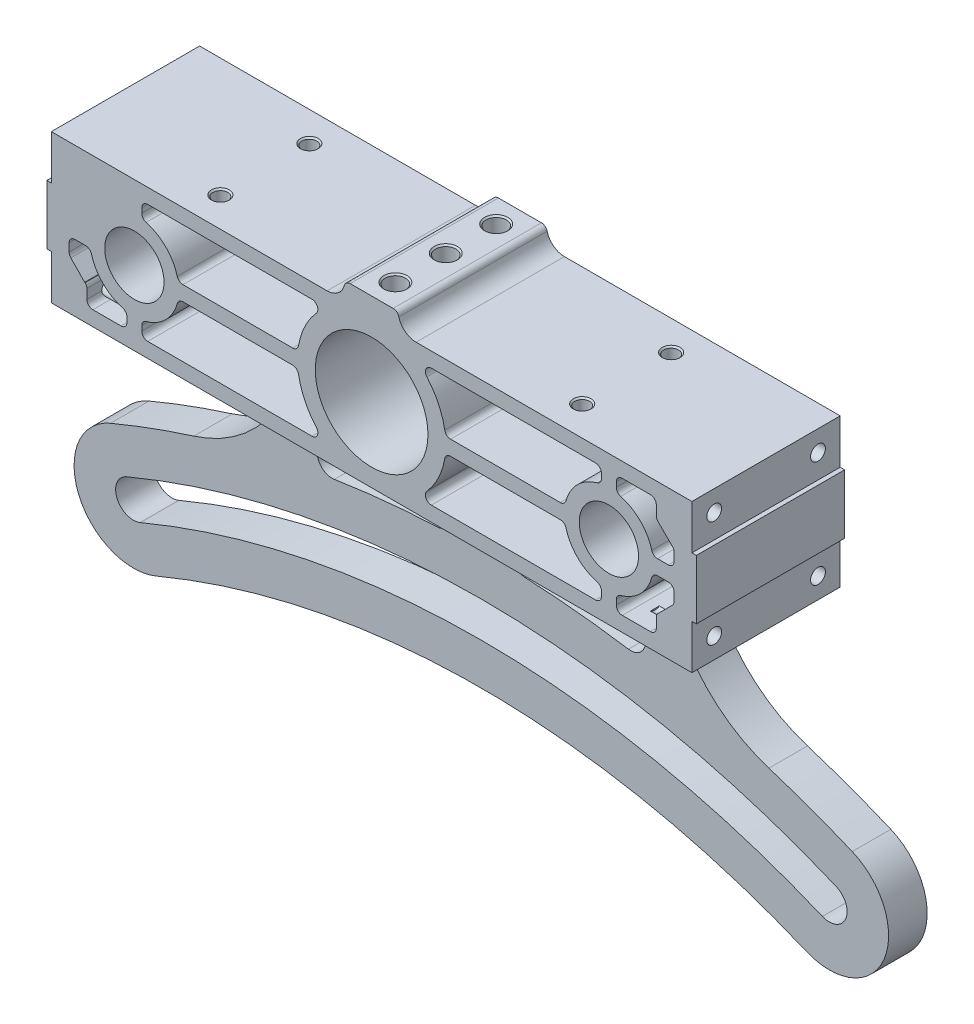
SolidWorks part; units mm, degrees
ref_plane "前视基准面" through (0, 0, 0) normal (0, 0, 1) x (1, 0, 0)
ref_plane "上视基准面" through (0, 0, 0) normal (0, 1, 0) x (1, 0, 0)
ref_plane "右视基准面" through (0, 0, 0) normal (1, 0, 0) x (0, 0, -1)
sketch "草图1" plane through (0, 0, 0) normal (0, 0, 1) x (1, 0, 0)
  line L0 (974.4145, 1221.1754) -> (974.4145, 1203.8318)
  line L1 (994.4145, 1221.1754) -> (994.4145, 1203.8318)
  line L2 (994.4145, 1203.8318) -> (994.2313, 1203.7782)
  line L3 (883.0002, 1252.5896) -> (887.6615, 1247.7952)
  line L4 (887.8287, 1247.7611) -> (887.6615, 1247.7952)
  line L5 (884.4145, 1258.6754) -> (888.0209, 1258.6754)
  line L6 (887.8287, 1274.5896) -> (883.0002, 1269.7611)
  line L7 (920.8081, 1258.6754) -> (957.7921, 1258.6754)
  line L8 (920.8081, 1263.6754) -> (957.7921, 1263.6754)
  line L9 (1011.0368, 1263.6754) -> (1048.0209, 1263.6754)
  line L10 (1011.0368, 1258.6754) -> (1048.0209, 1258.6754)
  line L11 (1048.0209, 1258.6754) -> (1048.107, 1258.6965)
  line L12 (1081.0002, 1274.5896) -> (1085.8287, 1269.7611)
  line L13 (1080.8081, 1263.6754) -> (1084.4145, 1263.6754)
  line L14 (1085.8287, 1252.5896) -> (1081.0002, 1247.7611)
  line L15 (1080.8081, 1258.6754) -> (1084.4145, 1258.6754)
  line L67 (865.3441, 1261.1754) -> (1103.3353, 1261.1754) construction
  line L70 (884.4145, 1263.6754) -> (888.0209, 1263.6754) construction
  line L95 (1092.4145, 1251.1754) -> (1093.9145, 1251.1754)
  line L96 (1092.4145, 1271.1754) -> (1093.9145, 1271.1754)
  line L97 (1092.4145, 1251.1754) -> (1092.4145, 1236.1754)
  line L98 (876.4145, 1251.1754) -> (876.4145, 1236.1754)
  line L99 (874.9145, 1251.1754) -> (876.4145, 1251.1754)
  line L100 (874.9145, 1271.1754) -> (876.4145, 1271.1754)
  line L101 (876.4145, 1236.1754) -> (916.1814, 1236.1754)
  line L102 (947.3848, 1226.1754) -> (969.4145, 1226.1754)
  line L103 (1052.6475, 1236.1754) -> (1092.4145, 1236.1754)
  line L104 (890.4145, 1241.1754) -> (899.9145, 1241.1754)
  line L105 (908.9145, 1241.1754) -> (964.2899, 1241.1754)
  line L106 (1004.5391, 1241.1754) -> (1059.9145, 1241.1754)
  line L107 (1068.9145, 1241.1754) -> (1078.4145, 1241.1754)
  line L108 (999.4145, 1226.1754) -> (1021.4441, 1226.1754)
  line L109 (876.4145, 1286.1754) -> (969.4145, 1286.1754)
  line L110 (999.4145, 1286.1754) -> (1092.4145, 1286.1754)
  line L111 (890.4145, 1281.1754) -> (899.9145, 1281.1754)
  line L112 (908.9145, 1281.1754) -> (964.2899, 1281.1754)
  line L113 (1004.5391, 1281.1754) -> (1059.9145, 1281.1754)
  line L114 (1068.9145, 1281.1754) -> (1078.4145, 1281.1754)
  line L115 (1092.4145, 1286.1754) -> (1092.4145, 1271.1754)
  line L116 (876.4145, 1286.1754) -> (876.4145, 1271.1754)
  line L117 (882.4145, 1268.3469) -> (882.4145, 1265.6754)
  line L118 (1093.9145, 1271.1754) -> (1093.9145, 1251.1754)
  line L119 (874.9145, 1271.1754) -> (874.9145, 1251.1754)
  line L120 (914.6033, 1205.0954) -> (924.614, 1220.8002)
  line L121 (929.8546, 1202.9759) -> (943.1685, 1223.8629)
  line L122 (1044.215, 1220.8002) -> (1054.2256, 1205.0954)
  line L123 (1025.6604, 1223.8629) -> (1038.9743, 1202.9759)
  line L124 (906.9145, 1277.569) -> (906.9145, 1279.1754)
  line L125 (901.9145, 1277.569) -> (901.9145, 1279.1754)
  line L126 (906.9145, 1244.7818) -> (906.9145, 1243.1754)
  line L127 (901.9145, 1244.7818) -> (901.9145, 1243.1754)
  line L128 (1066.9145, 1277.569) -> (1066.9145, 1279.1754)
  line L129 (1061.9145, 1277.569) -> (1061.9145, 1279.1754)
  line L130 (1066.9145, 1244.7818) -> (1066.9145, 1243.1754)
  line L131 (1061.9145, 1244.7818) -> (1061.9145, 1243.1754)
  line L132 (888.4145, 1279.1754) -> (888.4145, 1276.0038)
  line L133 (888.4145, 1246.3469) -> (888.4145, 1243.1754)
  line L134 (1080.4145, 1243.1754) -> (1080.4145, 1246.3469)
  line L135 (1080.4145, 1276.0038) -> (1080.4145, 1279.1754)
  line L139 (882.4145, 1254.0038) -> (882.4145, 1256.6754)
  line L141 (1086.4145, 1268.3469) -> (1086.4145, 1265.6754)
  line L143 (1086.4145, 1254.0038) -> (1086.4145, 1256.6754)
  line L157 (977.1604, 1292.1754) -> (991.6685, 1292.1754)
  line L185 (977.3713, 1216.1754) -> (991.3965, 1216.1754) construction
  line L186 (904.4145, 1239.0674) -> (904.4145, 1282.8084) construction
  line L187 (1064.4145, 1239.0674) -> (1064.4145, 1282.8084) construction
  circle A0 centre (984.4145, 1216.1754) radius 5
  arc A12 (884.4145, 1258.6754) -> (882.4145, 1256.6754) centre (884.4145, 1256.6754) ccw
  arc A13 (1086.4145, 1256.6754) -> (1084.4145, 1258.6754) centre (1084.4145, 1256.6754) ccw
  circle A14 centre (904.4145, 1261.1754) radius 10
  arc A15 (889.9495, 1257.2048) -> (900.4439, 1246.7104) centre (904.4145, 1261.1754) ccw
  arc A16 (908.3851, 1246.7104) -> (918.8794, 1257.2048) centre (904.4145, 1261.1754) ccw
  arc A17 (908.3851, 1246.7104) -> (906.9145, 1244.7818) centre (908.9145, 1244.7818) ccw
  arc A18 (901.9145, 1244.7818) -> (900.4439, 1246.7104) centre (899.9145, 1244.7818) ccw
  arc A19 (918.8794, 1265.1459) -> (908.3851, 1275.6403) centre (904.4145, 1261.1754) ccw
  arc A20 (900.4439, 1275.6403) -> (889.9495, 1265.1459) centre (904.4145, 1261.1754) ccw
  arc A21 (900.4439, 1275.6403) -> (901.9145, 1277.569) centre (899.9145, 1277.569) ccw
  arc A22 (906.9145, 1277.569) -> (908.3851, 1275.6403) centre (908.9145, 1277.569) ccw
  arc A23 (918.8794, 1265.1459) -> (920.8081, 1263.6754) centre (920.8081, 1265.6754) ccw
  arc A24 (920.8081, 1258.6754) -> (918.8794, 1257.2048) centre (920.8081, 1256.6754) ccw
  arc A25 (889.9495, 1257.2048) -> (888.0209, 1258.6754) centre (888.0209, 1256.6754) ccw
  arc A26 (888.0209, 1263.6754) -> (889.9495, 1265.1459) centre (888.0209, 1265.6754) ccw
  circle A27 centre (1064.4145, 1261.1754) radius 10
  arc A28 (1078.8794, 1265.1459) -> (1068.3851, 1275.6403) centre (1064.4145, 1261.1754) ccw
  arc A29 (1060.4439, 1275.6403) -> (1049.9495, 1265.1459) centre (1064.4145, 1261.1754) ccw
  arc A30 (1060.4439, 1275.6403) -> (1061.9145, 1277.569) centre (1059.9145, 1277.569) ccw
  arc A31 (1066.9145, 1277.569) -> (1068.3851, 1275.6403) centre (1068.9145, 1277.569) ccw
  arc A32 (1049.9495, 1257.2048) -> (1060.4439, 1246.7104) centre (1064.4145, 1261.1754) ccw
  arc A33 (1068.3851, 1246.7104) -> (1078.8794, 1257.2048) centre (1064.4145, 1261.1754) ccw
  arc A34 (1061.9145, 1244.7818) -> (1060.4439, 1246.7104) centre (1059.9145, 1244.7818) ccw
  arc A35 (1068.3851, 1246.7104) -> (1066.9145, 1244.7818) centre (1068.9145, 1244.7818) ccw
  arc A36 (1078.8794, 1265.1459) -> (1080.8081, 1263.6754) centre (1080.8081, 1265.6754) ccw
  arc A37 (1080.8081, 1258.6754) -> (1078.8794, 1257.2048) centre (1080.8081, 1256.6754) ccw
  arc A38 (1048.0209, 1263.6754) -> (1049.9495, 1265.1459) centre (1048.0209, 1265.6754) ccw
  arc A39 (1049.9495, 1257.2048) -> (1048.0209, 1258.6754) centre (1048.0209, 1256.6754) ccw
  arc A40 (974.4145, 1221.1754) -> (969.4145, 1226.1754) centre (969.4145, 1221.1754) ccw
  arc A41 (947.3848, 1226.1754) -> (943.1685, 1223.8629) centre (947.3848, 1221.1754) ccw
  arc A42 (1025.6604, 1223.8629) -> (1021.4441, 1226.1754) centre (1021.4441, 1221.1754) ccw
  arc A43 (999.4145, 1226.1754) -> (994.4145, 1221.1754) centre (999.4145, 1221.1754) ccw
  arc A44 (924.614, 1220.8002) -> (916.1814, 1236.1754) centre (916.1814, 1226.1754) ccw
  arc A45 (1052.6475, 1236.1754) -> (1044.215, 1220.8002) centre (1052.6475, 1226.1754) ccw
  arc A46 (901.9145, 1279.1754) -> (899.9145, 1281.1754) centre (899.9145, 1279.1754) ccw
  arc A47 (890.4145, 1281.1754) -> (888.4145, 1279.1754) centre (890.4145, 1279.1754) ccw
  arc A48 (908.9145, 1281.1754) -> (906.9145, 1279.1754) centre (908.9145, 1279.1754) ccw
  arc A49 (1061.9145, 1279.1754) -> (1059.9145, 1281.1754) centre (1059.9145, 1279.1754) ccw
  arc A50 (1068.9145, 1281.1754) -> (1066.9145, 1279.1754) centre (1068.9145, 1279.1754) ccw
  arc A51 (1080.4145, 1279.1754) -> (1078.4145, 1281.1754) centre (1078.4145, 1279.1754) ccw
  arc A52 (882.4145, 1265.6754) -> (884.4145, 1263.6754) centre (884.4145, 1265.6754) ccw
  arc A53 (883.0002, 1269.7611) -> (882.4145, 1268.3469) centre (884.4145, 1268.3469) ccw
  arc A54 (1131.4611, 1141.1019) -> (836.9631, 1140.8769) centre (984.4145, 876.1749) ccw construction
  arc A55 (1099.4106, 1150.0086) -> (869.4184, 1150.0086) centre (984.4145, 876.1749) ccw
  arc A56 (1104.0569, 1161.0726) -> (864.7721, 1161.0726) centre (984.4145, 876.1749) ccw
  arc A57 (1033.9906, 1195.3476) -> (999.1858, 1198.837) centre (984.4145, 876.1749) ccw
  arc A58 (994.4145, 1203.8318) -> (999.1858, 1198.837) centre (999.4145, 1203.8318) ccw
  arc A59 (1033.9906, 1195.3476) -> (1038.9743, 1202.9759) centre (1034.758, 1200.2884) ccw
  arc A60 (969.6431, 1198.837) -> (934.8383, 1195.3476) centre (984.4145, 876.1749) ccw
  arc A61 (969.6431, 1198.837) -> (974.4145, 1203.8318) centre (969.4145, 1203.8318) ccw
  arc A62 (929.8546, 1202.9759) -> (934.8383, 1195.3476) centre (934.0709, 1200.2884) ccw
  arc A63 (1093.9899, 1137.1007) -> (874.8391, 1137.1007) centre (984.4145, 876.1749) ccw
  arc A64 (1109.4775, 1173.9806) -> (1081.3785, 1184.2771) centre (984.4145, 876.1749) ccw
  arc A65 (1054.2256, 1205.0954) -> (1081.3785, 1184.2771) centre (1096.3884, 1231.971) ccw
  arc A66 (887.4504, 1184.2771) -> (859.3514, 1173.9806) centre (984.4145, 876.1749) ccw
  arc A67 (887.4504, 1184.2771) -> (914.6033, 1205.0954) centre (872.4405, 1231.971) ccw
  arc A68 (1099.4106, 1150.0086) -> (1104.0569, 1161.0726) centre (1101.7337, 1155.5406) ccw
  arc A69 (1093.9899, 1137.1007) -> (1109.4775, 1173.9806) centre (1101.7337, 1155.5406) ccw
  arc A70 (864.7721, 1161.0726) -> (869.4184, 1150.0086) centre (867.0952, 1155.5406) ccw
  arc A71 (859.3514, 1173.9806) -> (874.8391, 1137.1007) centre (867.0952, 1155.5406) ccw
  arc A72 (906.9145, 1243.1754) -> (908.9145, 1241.1754) centre (908.9145, 1243.1754) ccw
  arc A73 (899.9145, 1241.1754) -> (901.9145, 1243.1754) centre (899.9145, 1243.1754) ccw
  arc A74 (1066.9145, 1243.1754) -> (1068.9145, 1241.1754) centre (1068.9145, 1243.1754) ccw
  arc A75 (1059.9145, 1241.1754) -> (1061.9145, 1243.1754) centre (1059.9145, 1243.1754) ccw
  arc A76 (887.8287, 1274.5896) -> (888.4145, 1276.0038) centre (886.4145, 1276.0038) ccw
  arc A77 (888.4145, 1243.1754) -> (890.4145, 1241.1754) centre (890.4145, 1243.1754) ccw
  arc A78 (1078.4145, 1241.1754) -> (1080.4145, 1243.1754) centre (1078.4145, 1243.1754) ccw
  arc A79 (1081.0002, 1247.7611) -> (1080.4145, 1246.3469) centre (1082.4145, 1246.3469) ccw
  arc A80 (1080.4145, 1276.0038) -> (1081.0002, 1274.5896) centre (1082.4145, 1276.0038) ccw
  arc A81 (888.4145, 1246.3469) -> (887.8287, 1247.7611) centre (886.4145, 1246.3469) ccw
  arc A82 (882.4145, 1254.0038) -> (883.0002, 1252.5896) centre (884.4145, 1254.0038) ccw
  arc A83 (1086.4145, 1268.3469) -> (1085.8287, 1269.7611) centre (1084.4145, 1268.3469) ccw
  arc A84 (1084.4145, 1263.6754) -> (1086.4145, 1265.6754) centre (1084.4145, 1265.6754) ccw
  arc A85 (1085.8287, 1252.5896) -> (1086.4145, 1254.0038) centre (1084.4145, 1254.0038) ccw
  circle A86 centre (984.4145, 1261.1754) radius 19
  arc A87 (959.7641, 1257.0087) -> (965.7806, 1244.5087) centre (984.4145, 1261.1754) ccw
  arc A88 (959.7641, 1257.0087) -> (957.7921, 1258.6754) centre (957.7921, 1256.6754) ccw
  arc A89 (964.2899, 1241.1754) -> (965.7806, 1244.5087) centre (964.2899, 1243.1754) ccw
  arc A90 (1003.0484, 1244.5087) -> (1009.0648, 1257.0087) centre (984.4145, 1261.1754) ccw
  arc A91 (1003.0484, 1244.5087) -> (1004.5391, 1241.1754) centre (1004.5391, 1243.1754) ccw
  arc A92 (1011.0368, 1258.6754) -> (1009.0648, 1257.0087) centre (1011.0368, 1256.6754) ccw
  arc A93 (1009.0648, 1265.342) -> (1003.0484, 1277.842) centre (984.4145, 1261.1754) ccw
  arc A94 (1009.0648, 1265.342) -> (1011.0368, 1263.6754) centre (1011.0368, 1265.6754) ccw
  arc A95 (1004.5391, 1281.1754) -> (1003.0484, 1277.842) centre (1004.5391, 1279.1754) ccw
  arc A96 (965.7806, 1277.842) -> (959.7641, 1265.342) centre (984.4145, 1261.1754) ccw
  arc A97 (957.7921, 1263.6754) -> (959.7641, 1265.342) centre (957.7921, 1265.6754) ccw
  arc A98 (965.7806, 1277.842) -> (964.2899, 1281.1754) centre (964.2899, 1279.1754) ccw
  arc A99 (969.4145, 1286.1754) -> (975.2239, 1290.6754) centre (969.4145, 1292.1754) ccw
  arc A100 (977.1604, 1292.1754) -> (975.2239, 1290.6754) centre (977.1604, 1290.1754) ccw
  arc A101 (993.605, 1290.6754) -> (999.4145, 1286.1754) centre (999.4145, 1292.1754) ccw
  arc A102 (993.605, 1290.6754) -> (991.6685, 1292.1754) centre (991.6685, 1290.1754) ccw
  dimension "D1" = 10
extrude "拉伸1" add sketch "草图1" against normal blind 50
sketch "草图2" plane through (1093.9145, 0, 0) normal (1, 0, 0) x (0, 0, -1)
  line L0 (-1.9815, 1236.1754) -> (27, 1236.1754)
  line L1 (37, 1226.1754) -> (37, 1128.1832)
  line L2 (37, 1128.1832) -> (-10.9314, 1128.1832)
  line L3 (-10.9314, 1128.1832) -> (-10.9314, 1236.1754)
  line L4 (-10.9314, 1236.1754) -> (-1.9815, 1236.1754)
  line L5 (50, 1223.8629) -> (50, 1202.9759) construction
  arc A0 (37, 1226.1754) -> (27, 1236.1754) centre (27, 1226.1754) ccw
  point P2 (50, 1213.4194)
  dimension "D3" = 10
  dimension "D1" = 50
  dimension "D2" = 13
extrude "拉伸2" cut sketch "草图2" against normal mid plane 1000
sketch "草图3" plane through (1092.4145, 0, 0) normal (1, 0, 0) x (0, 0, -1)
  line L0 (0, 1261.1754) -> (53.4498, 1261.1754) construction
  line L1 (0, 1271.1754) -> (0, 1251.1754) construction
  line L2 (50, 1236.1754) -> (0, 1236.1754) construction
  circle A0 centre (7.5, 1243.1754) radius 2.5
  circle A1 centre (42.5, 1243.1754) radius 2.5
  circle A2 centre (42.5, 1279.1754) radius 2.5
  circle A3 centre (7.5, 1279.1754) radius 2.5
  dimension "D1" = 5
  dimension "D2" = 5
  dimension "D3" = 5
  dimension "D4" = 5
  dimension "D5" = 35
  dimension "D6" = 36
  dimension "D7" = 7.5
  dimension "D9" = 18
  dimension "D10" = 18
  dimension "D11" = 35
  dimension "D12" = 36
  dimension "D8" = 25
extrude "拉伸3" cut sketch "草图3" against normal blind 20
ref_plane "基准面2" through (984.4145, 0, 0) normal (1, 0, 0) x (0, 0, -1)
mirror "镜向1" about plane through (984.4145, 0, 0) normal (1, 0, 0) of "拉伸3"
sketch "草图4" plane through (0, 1286.1754, 0) normal (0, 1, 0) x (1, 0, 0)
  line L1 (999.4145, 0) -> (1092.4145, 0) construction
  line L2 (984.4145, -8.25) -> (984.4145, 8.25) construction
  circle A0 centre (923.4145, 40) radius 2.5
  circle A1 centre (923.4145, 10) radius 2.5
  circle A2 centre (1045.4145, 40) radius 2.5
  circle A3 centre (1045.4145, 10) radius 2.5
  dimension "D1" = 5
  dimension "D2" = 5
  dimension "D3" = 5
  dimension "D4" = 5
  dimension "D5" = 10
  dimension "D6" = 30
  dimension "D7" = 10
  dimension "D8" = 30
  dimension "D9" = 122
  dimension "D10" = 61
extrude "拉伸4" cut sketch "草图4" against normal blind 20
chamfer "倒角1" distance 0.5 angle 45 4 edges at (1045.4145, 1286.1754, -7.5) (1045.4145, 1286.1754, -37.5) (923.4145, 1286.1754, -7.5) (923.4145, 1286.1754, -37.5)
sketch "草图5" plane through (0, 1292.1754, 0) normal (0, 1, 0) x (1, 0, 0)
  line L0 (984.4145, -8.25) -> (984.4145, 8.25) construction
  line L1 (999.4145, 0) -> (1092.4145, 0) construction
  circle A0 centre (984.4145, 42) radius 3.425
  circle A1 centre (984.4145, 25) radius 3.425
  circle A2 centre (984.4145, 8) radius 3.425
  dimension "D1" = 6.85
  dimension "D2" = 6.85
  dimension "D3" = 6.85
  dimension "D4" = 8
  dimension "D5" = 17
  dimension "D6" = 17
extrude "拉伸5" cut sketch "草图5" against normal up to next
chamfer "倒角2" distance 0.5 angle 45 3 edges at (984.4145, 1292.1754, -4.575) (984.4145, 1292.1754, -21.575) (984.4145, 1292.1754, -38.575)
